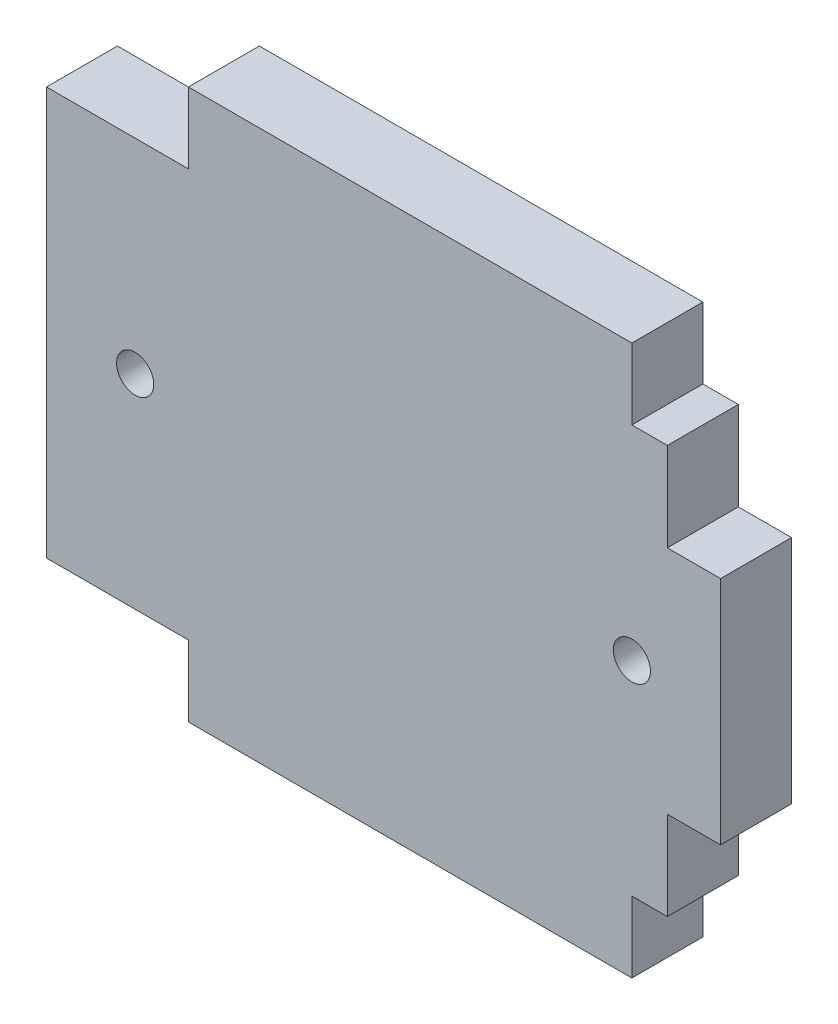
SolidWorks part; units mm, degrees
material "Acrílico (Impacto medio-alto)"
ref_plane "Alzado" through (0, 0, 0) normal (0, 0, 1) x (1, 0, 0)
ref_plane "Planta" through (0, 0, 0) normal (0, 1, 0) x (1, 0, 0)
ref_plane "Vista lateral" through (0, 0, 0) normal (1, 0, 0) x (0, 0, -1)
sketch "Croquis1" plane through (0, 0, 0) normal (0, 0, 1) x (1, 0, 0)
  line L0 (-35, 0) -> (-35, -4)
  line L1 (-35, -4) -> (-43, -4)
  line L2 (-35, -31) -> (-35, -27)
  line L3 (-35, -27) -> (-43, -27)
  line L4 (-43, -27) -> (-43, -4)
  line L5 (-35, -4) -> (-10, -4) construction
  line L6 (-35, 0) -> (-10, 0) construction
  line L7 (-10, 0) -> (-10, -4)
  line L8 (-35, -31) -> (-10, -31)
  line L9 (-10, -31) -> (-10, -27)
  line L10 (-10, -27) -> (-10, -22) construction
  line L11 (-10, -22) -> (-5, -22) construction
  line L12 (-5, -22) -> (-5, -9)
  line L13 (-5, -9) -> (-10, -9) construction
  line L14 (-10, -9) -> (-10, -4) construction
  line L15 (-7.5, -8) -> (4.6496, -8) construction
  line L16 (4.6496, -23) -> (-7.5, -23) construction
  line L17 (-35, 0) -> (-10, 0)
  line L18 (-35, -27) -> (-10, -27) construction
  line L19 (-10, -27) -> (-8, -27)
  line L20 (-8, -27) -> (-8, -22)
  line L21 (-8, -9) -> (-8, -4)
  line L22 (-8, -4) -> (-10, -4)
  line L23 (-8, -9) -> (-5, -9)
  line L24 (-8, -22) -> (-5, -22)
  point P32 (-10.1873, -4)
  dimension "D1" = 8
  dimension "D2" = 1
  dimension "D3" = 1
  dimension "D4" = 5
  dimension "D5" = 2
extrude "Saliente-Extruir1" add sketch "Croquis1" along normal blind 4 contours L17 L7 L22 L21 L23 L12 L24 L20 L19 L9 L8 L2 L3 L4 L1 L0
sketch "Croquis2" plane through (0, 0, 4) normal (0, 0, 1) x (1, 0, 0)
  circle A0 centre (-38.0017, -15.5) radius 1.0477
  circle A1 centre (-9.9982, -15.5) radius 1.0477
extrude "Cortar-Extruir1" cut sketch "Croquis2" against normal up to next
